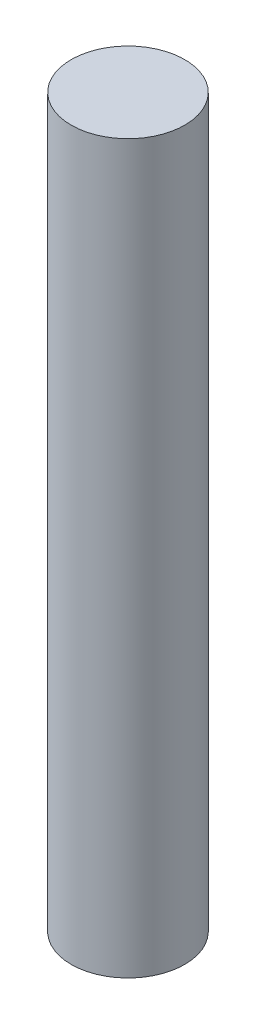
SolidWorks part; units mm, degrees
material "AISI 304"
ref_plane "Front Plane" through (0, 0, 0) normal (0, 0, 1) x (1, 0, 0)
ref_plane "Top Plane" through (0, 0, 0) normal (0, 1, 0) x (1, 0, 0)
ref_plane "Right Plane" through (0, 0, 0) normal (1, 0, 0) x (0, 0, -1)
sketch "Sketch1" plane through (0, 0, 0) normal (0, 1, 0) x (1, 0, 0)
  circle A0 centre (0, 0) radius 1.25
  dimension "D1" = 2.5
extrude "Boss-Extrude1" add sketch "Sketch1" along normal blind 16
